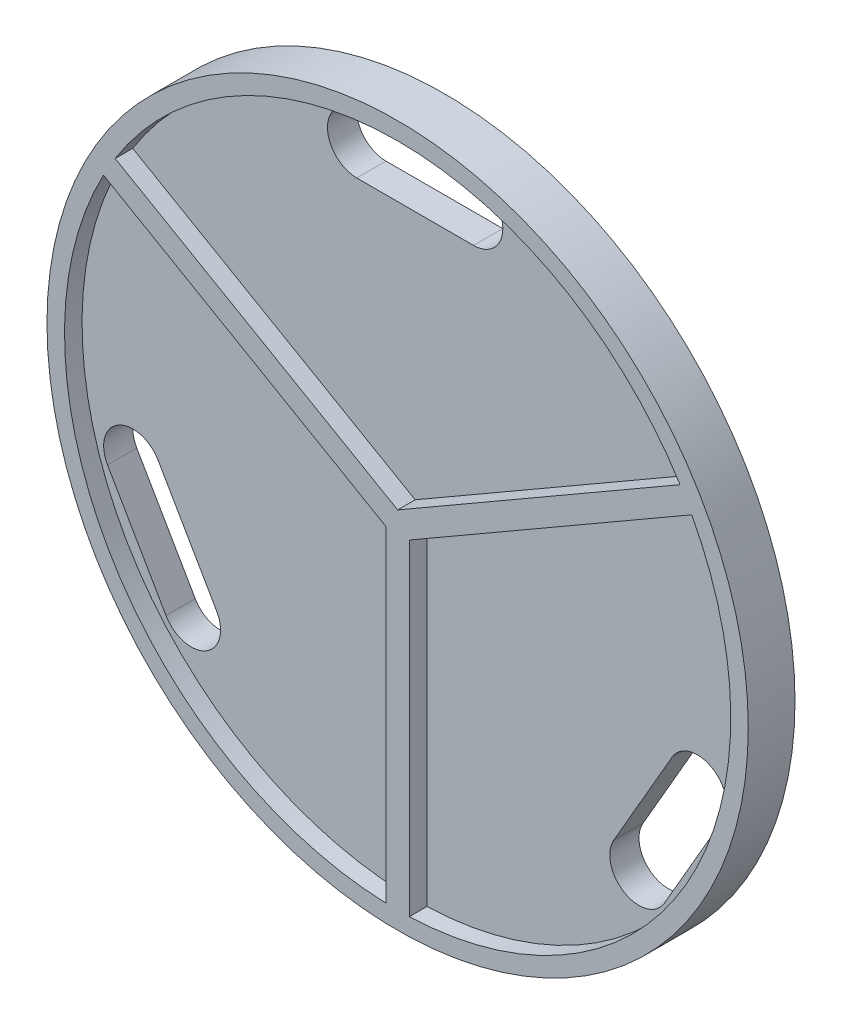
SolidWorks part; units mm, degrees
ref_plane "前视基准面" through (0, 0, 0) normal (0, 0, 1) x (1, 0, 0)
ref_plane "上视基准面" through (0, 0, 0) normal (0, 1, 0) x (1, 0, 0)
ref_plane "右视基准面" through (0, 0, 0) normal (1, 0, 0) x (0, 0, -1)
sketch "草图1" plane through (0, 0, 0) normal (0, 0, 1) x (1, 0, 0)
  line L0 (0, 60) -> (0, -60) construction
  line L1 (51.9615, 30) -> (-51.9615, -30) construction
  line L2 (-51.9615, 30) -> (51.9615, -30) construction
  line L3 (0, 0) -> (-34.641, -20) construction
  line L4 (-5, 8.6603) -> (5, -8.6603) construction
  line L5 (-39.641, -11.3397) -> (-29.641, -28.6603) construction
  line L6 (5, -8.6603) -> (-29.641, -28.6603) construction
  line L7 (-5, 8.6603) -> (-39.641, -11.3397) construction
  line L8 (-43.3013, -25) -> (-38.9711, -22.5) construction
  line L9 (-48.3013, -16.3397) -> (-38.3013, -33.6603) construction
  line L10 (-43.3013, -25) -> (-45.8013, -20.6699) construction
  line L11 (-48.3013, -16.3397) -> (-38.3013, -33.6603) construction
  line L12 (-43.9711, -13.8397) -> (-33.9711, -31.1603)
  line L13 (-52.6314, -18.8397) -> (-42.6314, -36.1603)
  line L14 (48.3013, -16.3397) -> (38.3013, -33.6603) construction
  line L15 (43.9711, -13.8397) -> (33.9711, -31.1603)
  line L16 (52.6314, -18.8397) -> (42.6314, -36.1603)
  line L17 (10, 50) -> (-10, 50) construction
  line L18 (10, 45) -> (-10, 45)
  line L19 (10, 55) -> (-10, 55)
  circle A0 centre (0, 0) radius 60
  arc A3 (-43.9711, -13.8397) -> (-52.6314, -18.8397) centre (-48.3013, -16.3397) ccw
  arc A4 (-42.6314, -36.1603) -> (-33.9711, -31.1603) centre (-38.3013, -33.6603) ccw
  arc A5 (43.9711, -13.8397) -> (52.6314, -18.8397) centre (48.3013, -16.3397) cw
  arc A6 (42.6314, -36.1603) -> (33.9711, -31.1603) centre (38.3013, -33.6603) cw
  arc A7 (10, 45) -> (10, 55) centre (10, 50) ccw
  arc A8 (-10, 55) -> (-10, 45) centre (-10, 50) ccw
  point P6 (0, 0)
  point P8 (0, 0)
  point P16 (-43.3013, -25)
  point P20 (-43.3013, -25)
  point P27 (-38.9711, -22.5)
  point P30 (-38.9711, -22.5)
  point P31 (43.3013, -25)
  point P38 (0, 50)
  dimension "D1" = 120
  dimension "D5" = 10
  dimension "D6" = 5
  dimension "D2" = 60
  dimension "D3" = 40
  dimension "D4" = 20
  dimension "D7" = 20
extrude "凸台-拉伸1" add sketch "草图1" along normal blind 5
sketch "草图2" plane through (0, 0, 5) normal (0, 0, 1) x (1, 0, 0)
  circle A0 centre (0, 0) radius 57
  circle A1 centre (0, 0) radius 60
extrude "凸台-拉伸2" add sketch "草图2" along normal blind 3
sketch "草图3" plane through (0, 0, 5) normal (0, 0, 1) x (1, 0, 0)
  line L0 (0, 0) -> (0, -57) construction
  line L1 (0, 0) -> (-49.3634, 28.5) construction
  line L2 (0, 0) -> (49.3634, 28.5) construction
  line L3 (0, 2.3094) -> (-48.3331, 30.2145)
  line L4 (-2, -1.1547) -> (-50.3331, 26.7504)
  line L5 (-1, -1.7321) -> (-50.3634, 26.7679) construction
  line L6 (1, 1.7321) -> (-48.3634, 30.2321) construction
  line L7 (2, -1.1547) -> (50.3331, 26.7504)
  line L8 (0, 2.3094) -> (48.3331, 30.2145)
  line L9 (2, -1.1547) -> (2, -56.9649)
  line L10 (-2, -1.1547) -> (-2, -56.9649)
  circle A0 centre (0, 0) radius 57 construction
  circle A1 centre (0, 0) radius 57
  circle M16 centre (0, 0) radius 57
  dimension "D4" = 114
  dimension "D1" = 120
  dimension "D2" = 2
  dimension "D3" = 2
extrude "凸台-拉伸3" add sketch "草图3" along normal up to surface (3 mm away) contours L4 L10 L9 L7 L8 L3 M16 up to face at (60, 0, 8)
